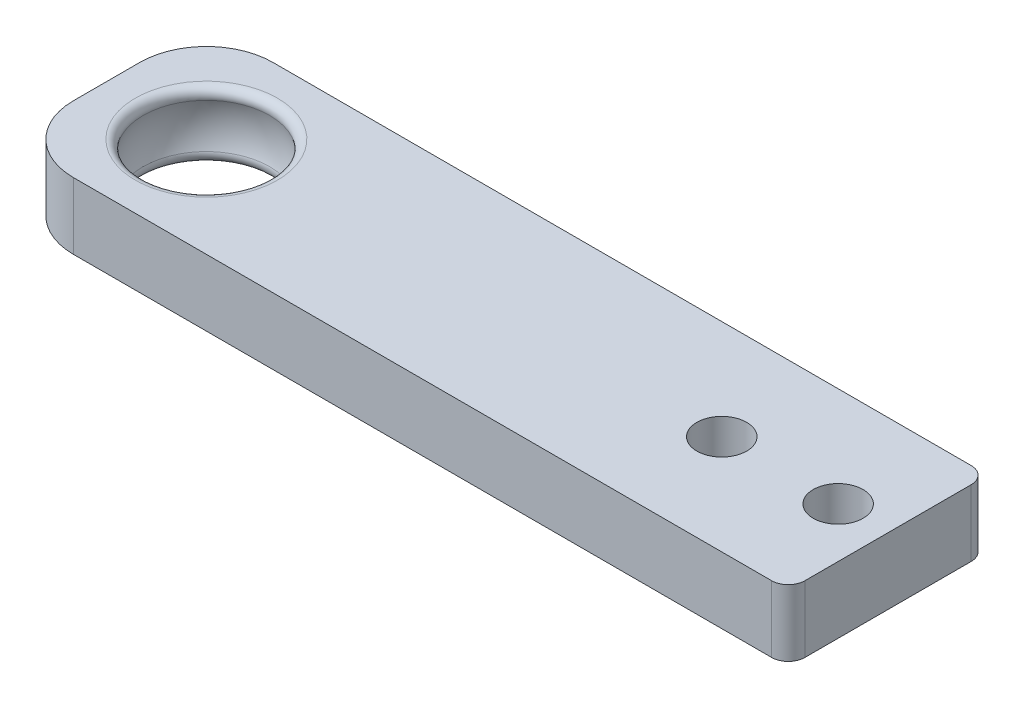
SolidWorks part; units mm, degrees
ref_plane "Front Plane" through (0, 0, 0) normal (0, 0, 1) x (1, 0, 0)
ref_plane "Top Plane" through (0, 0, 0) normal (0, 1, 0) x (1, 0, 0)
ref_plane "Right Plane" through (0, 0, 0) normal (1, 0, 0) x (0, 0, -1)
sketch "Sketch1" plane through (0, 0, 0) normal (0, 1, 0) x (1, 0, 0)
  line L1 (16, 6) -> (-16, 6)
  line L2 (16, 6) -> (16, -6)
  line L3 (16, -6) -> (-16, -6)
  line L4 (-16, 6) -> (-16, -6)
  line L5 (16, 6) -> (-16, -6) construction
  line L6 (16, -6) -> (-16, 6) construction
  point P0 (0, 0)
  dimension "D1" = 32
  dimension "D2" = 12
extrude "Boss-Extrude1" add sketch "Sketch1" along normal blind 4
sketch "Sketch2" plane through (0, 0, 0) normal (0, 0, 1) x (1, 0, 0)
  line L0 (-10, 4) -> (-10, 0)
  line L1 (-16, 4) -> (16, 4) construction
  line L2 (-16, 0) -> (16, 0) construction
  line L3 (-16, 4) -> (-16, 0) construction
  line L4 (-10, 4) -> (-13.5, 4)
  line L5 (-13.5, 0) -> (-10, 0)
  arc A0 (-13.5, 4) -> (-13.5, 0) centre (-10, 2) ccw
  dimension "D1" = 6
  dimension "D2" = 3.5
revolve "Cut-Revolve1" cut sketch "Sketch2" angle 360 about L0
fillet "Fillet1" radius 4 2 edges at (-16, 2, -6) (-16, 2, 6)
fillet "Fillet2" radius 0.5 2 edges at (-13.5, 4, 0) (-13.5, 0, 0)
sketch "Sketch3" plane through (16, 0, 0) normal (1, 0, 0) x (0, 0, -1)
  line L0 (-6, 4) -> (6, 4) construction
  line L1 (-6, 0) -> (6, 0) construction
  line L2 (-6, 4) -> (6, 4)
  line L3 (-6, 4) -> (-6, 0)
  line L4 (-6, 0) -> (6, 0)
  line L5 (6, 4) -> (6, 0)
  dimension "D1" = 12
  dimension "D2" = 6
extrude "Boss-Extrude2" add sketch "Sketch3" along normal blind 15
sketch "Sketch5" plane through (0, 4, 0) normal (0, 1, 0) x (1, 0, 0)
  line L0 (31, 6) -> (31, -6) construction
  circle A0 centre (21, 0) radius 1.5
  circle A1 centre (28, 0) radius 1.5
  dimension "D1" = 3
  dimension "D2" = 3
  dimension "D3" = 7
  dimension "D4" = 3
extrude "Cut-Extrude1" cut sketch "Sketch5" against normal through all
fillet "Fillet4" radius 1 2 edges at (31, 2, 6) (31, 2, -6)
